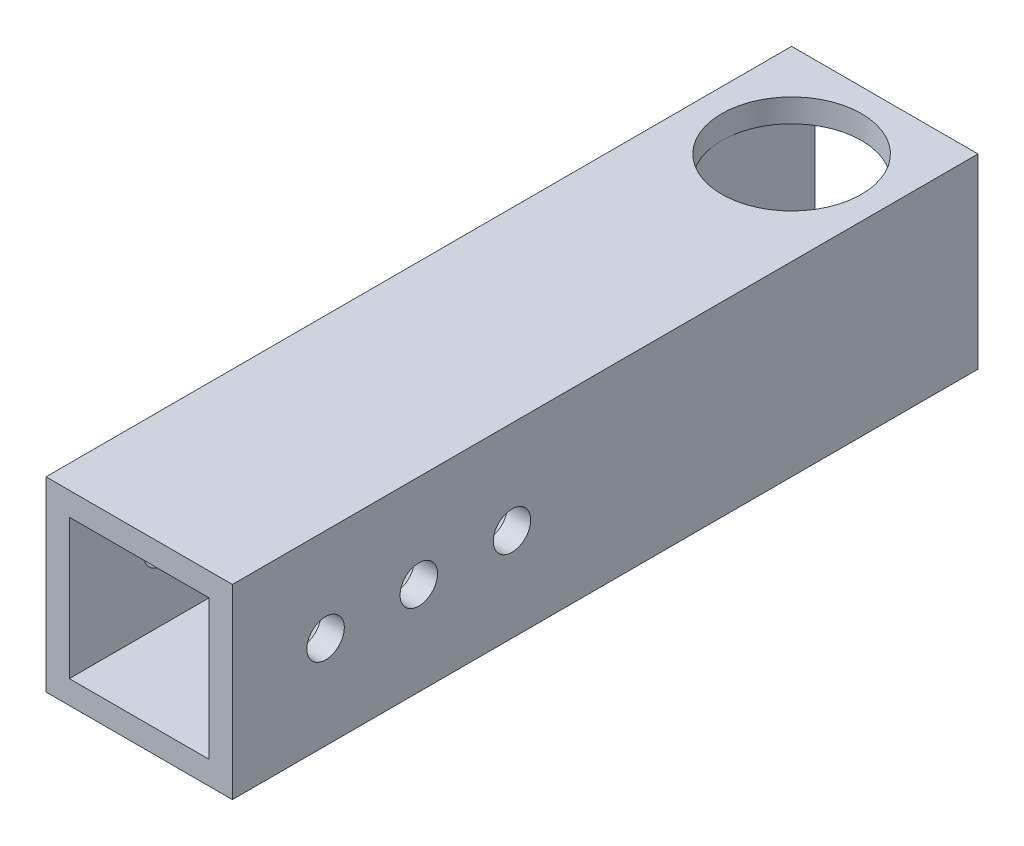
SolidWorks part; units mm, degrees
material "6061 Alloy"
ref_plane "Front" through (0, 0, 0) normal (0, 0, 1) x (1, 0, 0)
ref_plane "Top" through (0, 0, 0) normal (0, 1, 0) x (1, 0, 0)
ref_plane "Right" through (0, 0, 0) normal (1, 0, 0) x (0, 0, -1)
sketch "Sketch1" plane through (0, 0, 0) normal (0, 0, 1) x (1, 0, 0)
  line L1 (0, 0) -> (-25.4, 0)
  line L2 (0, 0) -> (0, 25.4)
  line L3 (0, 25.4) -> (-25.4, 25.4)
  line L4 (-25.4, 0) -> (-25.4, 25.4)
  dimension "D1" = 25.4
extrude "Extrude-Thin1" add sketch "Sketch1" along normal blind 101.6 thin
sketch "Sketch2" plane through (0, 0, 0) normal (0, -1, 0) x (-1, 0, 0)
  line L0 (25.4, 0) -> (0, 0) construction
  line L1 (0, -101.6) -> (0, 0) construction
  circle A0 centre (12.7, -12.7) radius 9.525
  dimension "D1" = 12.7
  dimension "D2" = 12.7
  dimension "D3" = 19.05
extrude "Cut-Extrude1" cut sketch "Sketch2" against normal through all
hole_wizard "#10 Clearance Hole1" positions "Sketch3" profile "Sketch4" hole size "#10" standard "ANSI Inch"
sketch "Sketch3" plane through (0, 0, 0) normal (1, 0, 0) x (0, 0, -1)
  line L0 (-101.6, 0) -> (-101.6, 25.4) construction
  line L1 (-101.6, 0) -> (0, 0) construction
  point P0 (-76.2, 12.7)
  point P2 (-88.9, 12.7)
  point P4 (-63.5, 12.7)
  point P10 (0, 0)
  dimension "D1" = 12.7
  dimension "D2" = 12.7
  dimension "D3" = 12.7
  dimension "D4" = 12.7
sketch "Sketch4" plane through (0, 12.7, 76.2) normal (0, 1, 0) x (0, 0, -1)
  line L0 (0, 0) -> (0, 26.9328)
  line L1 (0, 26.9328) -> (2.5527, 25.399)
  line L2 (2.5527, 25.399) -> (2.5527, 0)
  line L5 (2.5527, 0) -> (0, 0)
  line L10 (0, 26.9328) -> (-2.5527, 25.399) construction
  line L11 (0, -6.35) -> (0, 107.95) construction
  dimension "Hole Dia." = 5.1054
  dimension "Hole Depth" = 25.399
  dimension "Drill Angle" = 118
